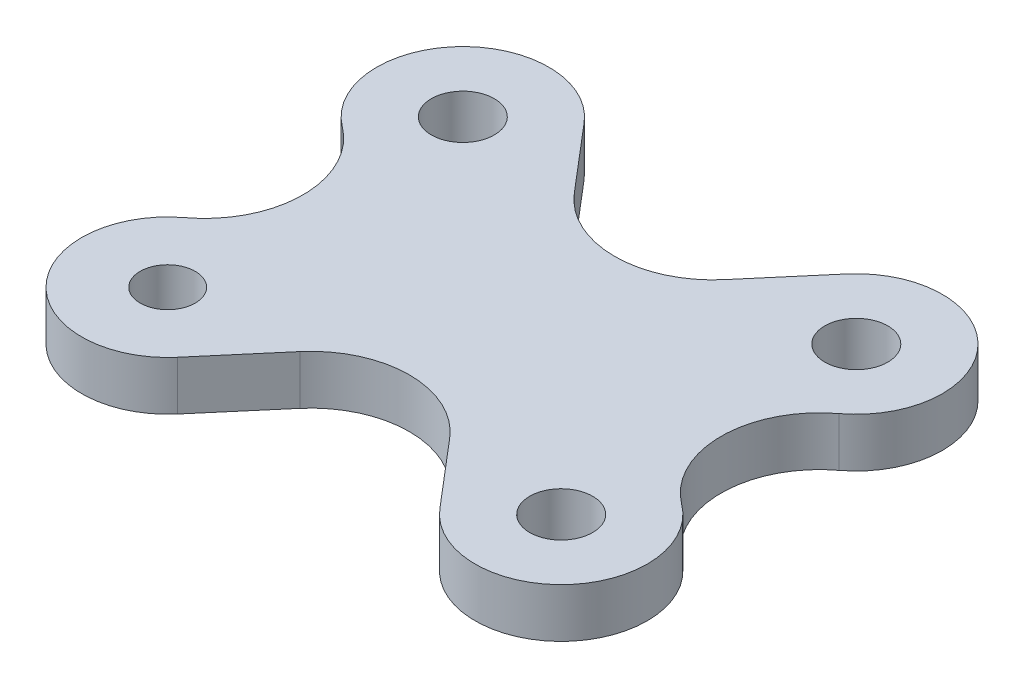
SolidWorks part; units mm, degrees
ref_plane "Front Plane" through (0, 0, 0) normal (0, 0, 1) x (1, 0, 0)
ref_plane "Top Plane" through (0, 0, 0) normal (0, 1, 0) x (1, 0, 0)
ref_plane "Right Plane" through (0, 0, 0) normal (1, 0, 0) x (0, 0, -1)
sketch "Sketch1" plane through (0, 0, 0) normal (0, 1, 0) x (1, 0, 0)
  line L0 (-12.7, -9.525) -> (12.7, 9.525) construction
  line L3 (12.7, -9.525) -> (-12.7, 9.525) construction
  line L10 (-8.4686, -13.126) -> (0, -3.175)
  line L11 (0, -3.175) -> (8.4686, -13.126)
  line L12 (14.6585, 4.3254) -> (3.175, 0)
  line L13 (3.175, 0) -> (14.6585, -4.3254)
  line L14 (8.4686, 13.126) -> (0, 3.175)
  line L15 (0, 3.175) -> (-8.4686, 13.126)
  line L16 (-14.6585, 4.3254) -> (-3.175, 0)
  line L17 (-3.175, 0) -> (-14.6585, -4.3254)
  line L18 (-3.175, 0) -> (3.175, 0) construction
  line L19 (0, -3.175) -> (0, 3.175) construction
  arc A4 (-14.6585, -4.3254) -> (-8.4686, -13.126) centre (-12.7, -9.525) ccw
  arc A5 (8.4686, -13.126) -> (14.6585, -4.3254) centre (12.7, -9.525) ccw
  arc A6 (14.6585, 4.3254) -> (8.4686, 13.126) centre (12.7, 9.525) ccw
  arc A7 (-8.4686, 13.126) -> (-14.6585, 4.3254) centre (-12.7, 9.525) ccw
  point P4 (0, 0)
  point P7 (0, 0)
  point P15 (2.9039, -0.223)
  point P16 (0, 3.415)
  point P17 (-2.6808, 0)
  point P18 (0.1535, -2.8098)
  point P19 (3.223, 0)
  point P25 (0, 0)
  point P27 (0, 0)
  point P28 (0, 3.5602)
  point P29 (-3.1723, 0)
  dimension "D3" = 11.1125
  dimension "D1" = 25.4
  dimension "D2" = 19.05
  dimension "D4" = 6.35
extrude "Boss-Extrude1" add sketch "Sketch1" along normal blind 3.175
fillet "Fillet1" radius 6.35 4 edges at (0, 1.5875, -3.175) (-3.175, 1.5875, 0) (3.175, 1.5875, 0) (0, 1.5875, 3.175)
sketch "Sketch2" plane through (0, 3.175, 0) normal (0, 1, 0) x (1, 0, 0)
  circle A0 centre (-12.7, 9.525) radius 2.032
  circle A1 centre (12.7, 9.525) radius 2.032
  circle A2 centre (12.7, -9.525) radius 2.032
  circle A3 centre (-12.7, -9.525) radius 1.778
  dimension "D1" = 4.064
  dimension "D2" = 3.556
extrude "Cut-Extrude1" cut sketch "Sketch2" against normal through all
